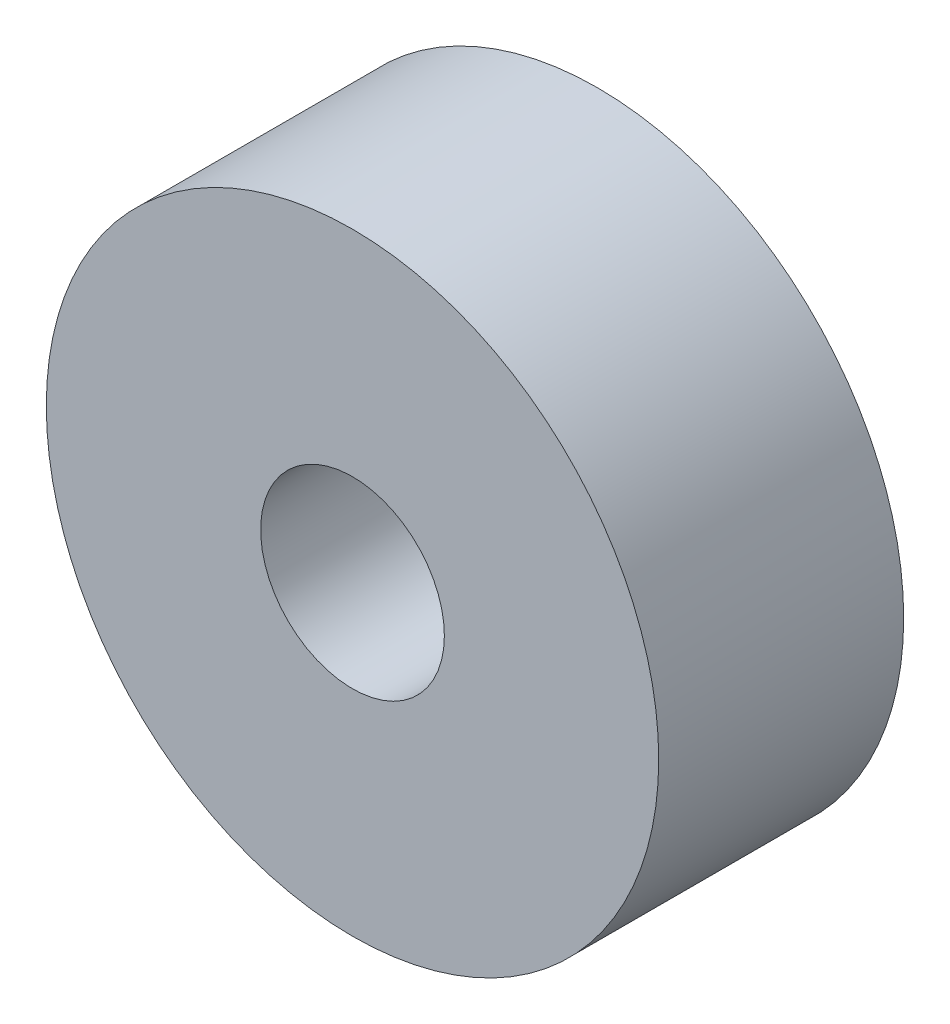
SolidWorks part; units mm, degrees
material "Plain Carbon Steel"
ref_plane "XY" through (0, 0, 0) normal (0, 0, 1) x (1, 0, 0)
ref_plane "XZ" through (0, 0, 0) normal (0, 1, 0) x (1, 0, 0)
ref_plane "YZ" through (0, 0, 0) normal (1, 0, 0) x (0, 0, -1)
sketch "Sketch1" plane through (0, 0, 0) normal (0, 0, 1) x (1, 0, 0)
  circle A0 centre (0, 0) radius 1.5
  circle A1 centre (0, 0) radius 5
  dimension "D1" = 10
  dimension "D2" = 3
extrude "Boss-Extrude1" add sketch "Sketch1" along normal mid plane 4
